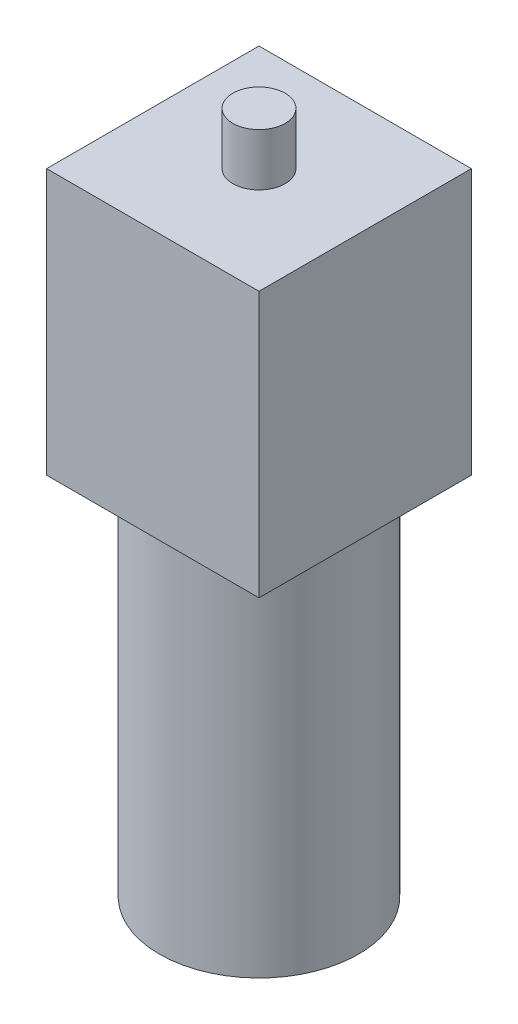
SolidWorks part; units mm, degrees
ref_plane "Front Plane" through (0, 0, 0) normal (0, 0, 1) x (1, 0, 0)
ref_plane "Top Plane" through (0, 0, 0) normal (0, 1, 0) x (1, 0, 0)
ref_plane "Right Plane" through (0, 0, 0) normal (1, 0, 0) x (0, 0, -1)
sketch "Sketch1" plane through (0, 0, 0) normal (0, 1, 0) x (1, 0, 0)
  circle A0 centre (0, 0) radius 19.05
extrude "Boss-Extrude1" add sketch "Sketch1" along normal blind 69.85
sketch "Sketch2" plane through (0, 69.85, 0) normal (0, 1, 0) x (1, 0, 0)
  line L1 (-20.32, 20.32) -> (20.32, 20.32)
  line L2 (-20.32, 20.32) -> (-20.32, -20.32)
  line L3 (-20.32, -20.32) -> (20.32, -20.32)
  line L4 (20.32, 20.32) -> (20.32, -20.32)
  line L5 (-20.32, 20.32) -> (20.32, -20.32) construction
  line L6 (-20.32, -20.32) -> (20.32, 20.32) construction
  point P0 (0, 0)
  dimension "D1" = 40.64
extrude "Boss-Extrude2" add sketch "Sketch2" along normal blind 50.8 contours L1 L4 L3 L2
sketch "Sketch3" plane through (0, 120.65, 0) normal (0, 1, 0) x (1, 0, 0)
  circle A0 centre (0, 0) radius 5
extrude "Boss-Extrude3" add sketch "Sketch3" along normal blind 10
